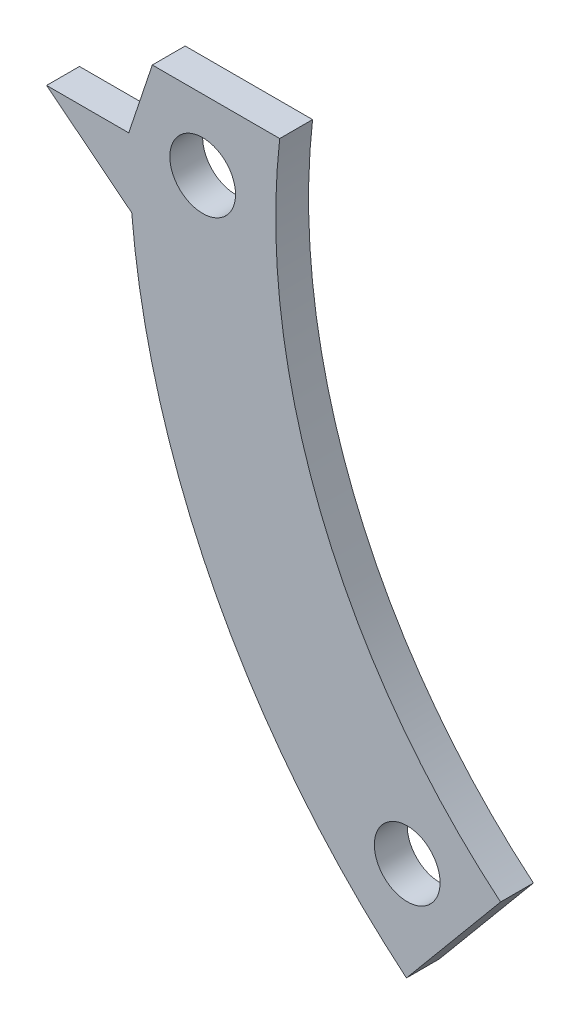
SolidWorks part; units mm, degrees
ref_plane "前视基准面" through (0, 0, 0) normal (0, 0, 1) x (1, 0, 0)
ref_plane "上视基准面" through (0, 0, 0) normal (0, 1, 0) x (1, 0, 0)
ref_plane "右视基准面" through (0, 0, 0) normal (1, 0, 0) x (0, 0, -1)
sketch "草图3" plane through (0, 0, 0) normal (0, 0, 1) x (1, 0, 0)
  line L0 (0, 53.0098) -> (-52, 53.0098) construction
  line L3 (0, 10.5098) -> (0, 17.5098) construction
  line L10 (-24.3707, 23.7824) -> (-30.0993, 16.9122)
  line L13 (0, 53.0098) -> (-37.8117, 57.3043) construction
  line L14 (0, 53.0098) -> (-17.9819, 9.5857) construction
  line L24 (0, 53.0098) -> (-24.3707, 23.7824) construction
  line L36 (-37.8117, 57.3043) -> (-45.5658, 57.3043)
  line L40 (-45.5658, 57.3043) -> (-47, 53.0098)
  line L43 (-47, 53.0098) -> (-52, 53.0098)
  line L44 (-52, 53.0098) -> (-46.8193, 48.892)
  arc A15 (-37.8117, 57.3043) -> (-24.3707, 23.7824) centre (0, 53.0098) ccw
  arc A16 (-30.0993, 16.9122) -> (-46.8193, 48.892) centre (0, 53.0098) cw
  circle A17 centre (0, 53.0098) radius 42.5 construction
  circle A19 centre (-30.052, 22.9577) radius 2
  circle A20 centre (-42.5, 53.0098) radius 2
  circle A30 centre (0, 53.0098) radius 47 construction
  circle A31 centre (0, 53.0098) radius 38.0548 construction
extrude "凸台-拉伸1" add sketch "草图3" along normal blind 2
